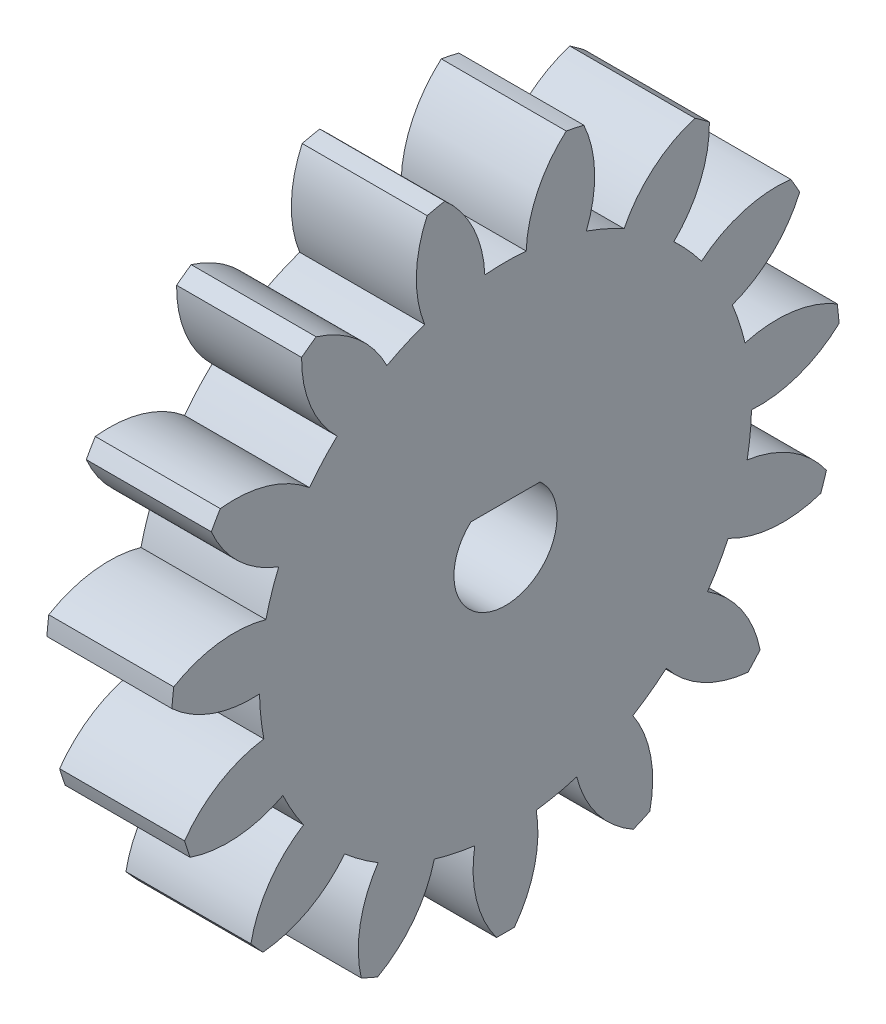
SolidWorks part; units mm, degrees
ref_plane "Plane1" through (0, 0, 0) normal (0, 0, 1) x (1, 0, 0)
ref_plane "Plane2" through (0, 0, 0) normal (0, 1, 0) x (1, 0, 0)
ref_plane "Plane3" through (0, 0, 0) normal (1, 0, 0) x (0, 0, -1)
sketch "HoldingSke" plane through (0, 0, 0) normal (0, 1, 0) x (1, 0, 0)
  line L0 (0, 0) -> (0.483, -0.1294)
  line L1 (-15, 0) -> (100, 0) construction
  line L2 (0, 0) -> (-2.1039, 2.3779)
  line L3 (0, 0) -> (-11.863, 4.5341)
  line L4 (0, 0) -> (8.3417, 2.2352)
  line L5 (0, 0) -> (-46.8476, -17.4728)
  line L6 (0, 0) -> (-5.2639, -3.5516)
  line L7 (-2.1039, 2.3779) -> (8.6586, 51.2059)
  line L8 (-76.2, 54.61) -> (-76.1, 54.61)
  line L9 (-71.009, 38.7566) -> (-53.1078, 45.2721)
  line L10 (-76.2, 71.12) -> (104.1128, 71.12)
  line L11 (0, 0) -> (-6.35, 0)
  line L12 (-76.2, 101.6) -> (-76.133, 101.6)
  line L13 (24.9733, 27.94) -> (52.9518, 28.4284)
  line L14 (24.9733, 27.94) -> (24.9743, 27.94)
  line L15 (24.9733, 27.94) -> (100.4006, 29.5858)
  line L16 (-63.627, -2) -> (-12.827, -2)
  circle A0 centre (0, 0) radius 0.4
  circle A1 centre (0, 0) radius 12.499
  circle A2 centre (0, 0) radius 37.5
  circle A3 centre (0, 0) radius 0.4
  dimension "MHD" = 24.998
  dimension "Hub_dia" = 75
  dimension "Bore" = 0.8
  dimension "MBD" = 0.8
  dimension "Num_teeth" = 15
  dimension "Pitch" = 0.5
  dimension "Overall_len" = 50
  dimension "Show_teeth" = 15
  dimension "Thickness" = 6.35
  dimension "OAL" = 50.0001
  dimension "T_dim" = 0.1
  dimension "Ap" = 20
  dimension "H" = 19.05
  dimension "Pitch_radius" = 180.3128
  dimension "Width" = 6.35
  dimension "Backlash" = 0.067
  dimension "Addendum_fac" = 1
  dimension "Dedendum_fac" = 1.25
  dimension "Clearance_fac" = 0.25
  dimension "Dedendum_add" = 0.001
  dimension "Module" = 2
sketch "BasProSke" plane through (0, 0, 0) normal (0, 1, 0) x (1, 0, 0)
  line L0 (-10, 0) -> (60, 0) construction
  line L1 (0, 0) -> (0, 17)
  line L2 (0, 0) -> (6.35, 0)
  line L3 (6.35, 0) -> (6.35, 17)
  line L4 (6.35, 17) -> (0, 17)
  dimension "Thickness" = 6.35
  dimension "Diameter" = 34
revolve "Base-Revolve" add sketch "BasProSke" angle 360 about L0
sketch "TooCutSke" plane through (0, 0, 0) normal (1, 0, 0) x (0, 0, -1)
  line L1 (0, 0) -> (0, 107) construction
  line L2 (0, 0) -> (-1.6851, 14.905) construction
  line L3 (0, 0) -> (-6.2081, 29.2069) construction
  line L4 (-1.6851, 14.905) -> (-3.1041, 14.6034) construction
  arc A0 (1.0501, 12.4548) -> (-1.0501, 12.4548) centre (0, 0) ccw
  arc A1 (3.1109, 16.7388) -> (-3.1109, 16.7388) centre (0, 0) ccw
  circle A2 centre (0, 0) radius 15 construction
  circle A3 centre (0, 0) radius 14.0954 construction
  arc A4 (-1.0501, 12.4548) -> (-3.1109, 16.7388) centre (-7.045, 12.2085) ccw
  arc A5 (3.1109, 16.7388) -> (1.0501, 12.4548) centre (7.045, 12.2085) ccw
  dimension "Root_dia" = 24.998
  dimension "Overcut_dia" = 34.0508
  dimension "Pitch_dia" = 30
  dimension "Base_dia" = 28.1908
  dimension "Flank_rad" = 6
  dimension "Half_ang" = 12
  dimension "Half_CT" = 1.4507
extrude "ToothCut" cut sketch "TooCutSke" along normal through all
fillet "Breaks" [suppressed] radius 0.04
fillet "RootFillets" [suppressed] radius 0.501
pattern_circular "TeethCuts" count 15 over 360 about axis through (0, 0, 0) along (1, 0, 0) of "ToothCut", "RootFillets", "Breaks"
sketch "HubNeaOneSke" plane through (0, 0, 0) normal (-1, 0, 0) x (0, 0, 1)
  circle A0 centre (0, 0) radius 12.499
  dimension "Diameter" = 24.998
extrude "HubNearOne" [suppressed] add sketch "HubNeaOneSke" along normal blind 43.6501
sketch "HubNeaBotSke" plane through (0, 0, 0) normal (-1, 0, 0) x (0, 0, 1)
  circle A0 centre (0, 0) radius 12.499
  dimension "Diameter" = 24.998
extrude "HubNearBoth" [suppressed] add sketch "HubNeaBotSke" along normal blind 21.825
ref_plane "FarPln" through (6.35, 0, 0) normal (1, 0, 0) x (0, 0, -1)
sketch "HubFarSke" plane through (6.35, 0, 0) normal (1, 0, 0) x (0, 0, -1)
  circle A0 centre (0, 0) radius 12.499
  dimension "Diameter" = 24.998
extrude "HubFar" [suppressed] add sketch "HubFarSke" along normal blind 21.825
sketch "BorSke" plane through (0, 0, 0) normal (1, 0, 0) x (0, 0, -1)
  circle A0 centre (0, 0) radius 0.4
  dimension "Diameter" = 0.8
extrude "Bore" cut sketch "BorSke" along normal mid plane 100.0001
sketch "KeySke" plane through (0, 0, 0) normal (1, 0, 0) x (0, 0, -1)
  line L0 (-0.05, 0) -> (-0.05, 0.5)
  line L1 (-0.05, 0.5) -> (0.05, 0.5)
  line L2 (0.05, 0.5) -> (0.05, 0)
  line L3 (0, 0) -> (0, 34) construction
  line L4 (-0.05, 0) -> (0.05, 0)
  dimension "Offset" = 0.5
  dimension "Width" = 0.1
extrude "Keyway" [suppressed] cut sketch "KeySke" along normal mid plane 100.0001
pattern_circular "Keyway2" [suppressed] count 2 every 90 about axis through (-10, 0, 0) along (1, 0, 0)
sketch "Sketch1" plane through (0, 0, 0) normal (-1, 0, 0) x (0, 0, 1)
  line L0 (-1.6599, 1.6916) -> (1.6599, 1.6916) construction
  line L1 (-1.7591, 1.9416) -> (1.7591, 1.9416)
  circle A0 centre (0, 0) radius 2.37 construction
  arc A1 (-1.6599, 1.6916) -> (1.6599, 1.6916) centre (0, 0) ccw construction
  arc A2 (-1.7591, 1.9416) -> (1.7591, 1.9416) centre (0, 0) ccw
  dimension "D1" = 4.74
  dimension "D2" = 1.6916
  dimension "D3" = 0.25
extrude "Cut-Extrude1" cut sketch "Sketch1" against normal up to next contours L0 A0 | A2 L1
equation "' \"Module@HoldingSke\" = 6.35"
equation "' \"Num_teeth@HoldingSke\" = 12"
equation "' \"Ap@HoldingSke\" =  20"
equation "' \"Ap@HoldingSke\" = 20"
equation "' \"Width@HoldingSke\" = 0.5 * 25.4"
equation "' \"Hub_dia@HoldingSke\"= 1 * 25.4"
equation "' \"Hub_dia@HoldingSke\" = 1 * 25.4"
equation "' \"Overall_len@HoldingSke\" = 1.0 * 25.4"
equation "' \"Bore@HoldingSke\" = 0.75 * 25.4"
equation "' \"T_dim@HoldingSke\" = 0.1 * 25.4"
equation "' \"Width@KeySke\" = 0.25 * 25.4"
equation "' \"Show_teeth@HoldingSke\" = 13"
equation "' \"Backlash@HoldingSke\" = 0.009 * 25.4"
equation "' \"Addendum_fac@HoldingSke\" = 1.0"
equation "' \"Dedendum_fac@HoldingSke\" = 1.25"
equation "' \"Dedendum_add@HoldingSke\" = 0.00005 * 25.4"
equation "' \"Clearance_fac@HoldingSke\" = 0.25"
equation "\"Pitch@HoldingSke\" = 1 / \"Module@HoldingSke\""
equation "\"Overcut_dia@TooCutSke\" = (\"Num_teeth@HoldingSke\" + 2 * \"Addendum_fac@HoldingSke\") / \"Pitch@HoldingSke\" + 0.002 * 25.4"
equation "\"Pitch_dia@TooCutSke\" = \"Num_teeth@HoldingSke\" / \"Pitch@HoldingSke\""
equation "\"Base_dia@TooCutSke\" = \"Num_teeth@HoldingSke\" / \"Pitch@HoldingSke\" * cos((\"Ap@HoldingSke\"  * 3.14159265 / 180))"
equation "\"Root_dia@TooCutSke\" = (\"Num_teeth@HoldingSke\" + 2) / \"Pitch@HoldingSke\" - 2 * (\"Addendum_fac@HoldingSke\" + \"Dedendum_fac@HoldingSke\") / \"Pitch@HoldingSke\" - \"Dedendum_add@HoldingSke\" * 2"
equation "\"Half_ang@TooCutSke\" = 180 / \"Num_teeth@HoldingSke\""
equation "\"Half_CT@TooCutSke\" = \"Num_teeth@HoldingSke\" / \"Pitch@HoldingSke\" * sin((3.14159265 / 2 / \"Num_teeth@HoldingSke\")) / 2 - 7 * \"Backlash@HoldingSke\" / 4"
equation "\"Flank_rad@TooCutSke\" = \"Num_teeth@HoldingSke\" / \"Pitch@HoldingSke\" / 5"
equation "\"Radius@RootFillets\" = \"Clearance_fac@HoldingSke\" / \"Pitch@HoldingSke\" + \"Dedendum_add@HoldingSke\""
equation "\"Break_rad@Breaks\" = 0.02 / \"Pitch@HoldingSke\""
equation "\"Thickness@HoldingSke\" = \"Width@HoldingSke\""
equation "\"OAL@HoldingSke\" = \"Thickness@HoldingSke\""
equation "\"MHD@HoldingSke\" = (\"Num_teeth@HoldingSke\" + 2) / \"Pitch@HoldingSke\" - 2 * (\"Addendum_fac@HoldingSke\" + \"Dedendum_fac@HoldingSke\")  / \"Pitch@HoldingSke\" - \"Dedendum_add@HoldingSke\" * 2"
equation "\"MBD@HoldingSke\" = (\"Num_teeth@HoldingSke\" + 2) / \"Pitch@HoldingSke\" - 2 * (\"Addendum_fac@HoldingSke\" + \"Dedendum_fac@HoldingSke\")  / \"Pitch@HoldingSke\" - \"Dedendum_add@HoldingSke\" * 2 - 0.002 * 25.4"
equation "\"MHD@HoldingSke\" = ((sgn( \"MHD@HoldingSke\" - \"Hub_dia@HoldingSke\" )-1)*( \"MHD@HoldingSke\" - \"Hub_dia@HoldingSke\" ))/-2+ \"Hub_dia@HoldingSke\""
equation "\"MBD@HoldingSke\" = ((sgn( \"MBD@HoldingSke\" - \"Bore@HoldingSke\" )-1)*( \"MBD@HoldingSke\" - \"Bore@HoldingSke\" ))/-2+ \"Bore@HoldingSke\""
equation "\"OAL@HoldingSke\" = ((sgn( \"OAL@HoldingSke\" - \"Overall_len@HoldingSke\" )+1)*( \"OAL@HoldingSke\" - \"Overall_len@HoldingSke\" ))/2 + \"Overall_len@HoldingSke\" + 0.000002 * 25.4"
equation "\"Num_teeth@TeethCuts\" = int( \"Show_teeth@HoldingSke\" ) + 1"
equation "\"Num_teeth@TeethCuts\" = ((sgn( \"Num_teeth@TeethCuts\" - \"Num_teeth@HoldingSke\" )-1)*( \"Num_teeth@TeethCuts\" - \"Num_teeth@HoldingSke\" ))/-2+ \"Num_teeth@HoldingSke\""
equation "\"Num_teeth@TeethCuts\" = ((sgn( \"Num_teeth@TeethCuts\" - 2.0)+1)*( \"Num_teeth@TeethCuts\" - 2.0))/2 +2.0"
equation "\"Angle@TeethCuts\" = 360.0 / \"Num_teeth@HoldingSke\""
equation "\"Diameter@BasProSke\" = (\"Num_teeth@HoldingSke\" + 2 * \"Addendum_fac@HoldingSke\") / \"Pitch@HoldingSke\""
equation "\"Thickness@BasProSke\"  = \"Thickness@HoldingSke\""
equation "' \"Fillet_rad@BasProSke\" =  \"Thickness@HoldingSke\" * 0.05"
equation "' \"Fillet_rad@BasProSke\" = \"Thickness@HoldingSke\" * 0.05"
equation "\"MHD@HoldingSke\" = ((sgn( \"MHD@HoldingSke\" - \"Root_dia@TooCutSke\" )-1)*( \"MHD@HoldingSke\" - \"Root_dia@TooCutSke\" ))/-2+ \"Root_dia@TooCutSke\""
equation "\"Diameter@HubNeaOneSke\" = \"MHD@HoldingSke\""
equation "\"Length@HubNearOne\" = \"OAL@HoldingSke\" - \"Thickness@BasProSke\""
equation "\"Diameter@HubNeaBotSke\" = \"MHD@HoldingSke\""
equation "\"Length@HubNearBoth\" = ( \"OAL@HoldingSke\" - \"Thickness@BasProSke\" ) / 2.0"
equation "\"Thickness@FarPln\" = \"Thickness@BasProSke\""
equation "\"Diameter@HubFarSke\" = \"MHD@HoldingSke\""
equation "\"Length@HubFar\" = ( \"OAL@HoldingSke\" - \"Thickness@BasProSke\" ) / 2.0"
equation "\"Diameter@BorSke\" = \"MBD@HoldingSke\""
equation "\"D1@Bore\" = \"OAL@HoldingSke\" * 2.0"
equation "\"D1@Keyway\" = \"OAL@HoldingSke\" * 2.0"
equation "\"Offset@KeySke\" = \"T_dim@HoldingSke\" + \"MBD@HoldingSke\" / 2.0"
